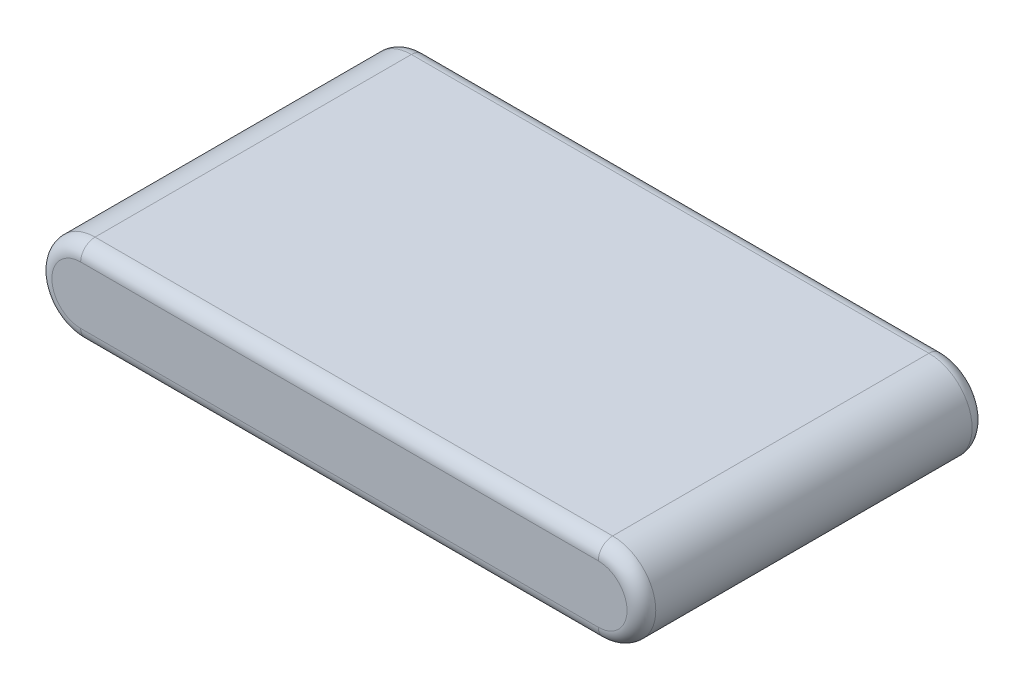
SolidWorks part; units mm, degrees
ref_plane "Plano frontal" through (0, 0, 0) normal (0, 0, 1) x (1, 0, 0)
ref_plane "Plano superior" through (0, 0, 0) normal (0, 1, 0) x (1, 0, 0)
ref_plane "Plano direito" through (0, 0, 0) normal (1, 0, 0) x (0, 0, -1)
sketch "Esboço1" plane through (0, 0, 0) normal (0, 0, 1) x (1, 0, 0)
  line L4 (0, 0) -> (0, 0.8933) construction
  line L7 (9, 0) -> (-9, 0) construction
  line L8 (9, 1.5) -> (-9, 1.5)
  line L9 (9, -1.5) -> (-9, -1.5)
  arc A6 (-9, -1.5) -> (-9, 1.5) centre (-9, 0) cw
  arc A7 (9, 1.5) -> (9, -1.5) centre (9, 0) cw
extrude "Ressalto-extrusão1" add sketch "Esboço1" along normal blind 12
fillet "Filete1" radius 0.5 8 edges at (0, 1.5, 0) (-10.5, 0, 0) (0, -1.5, 0) (10.5, 0, 0) (0, -1.5, 12) (-10.5, 0, 12) (0, 1.5, 12) (10.5, 0, 12)
sketch "Esboço2" plane through (0, 0, 12) normal (0, 0, 1) x (1, 0, 0)
  line L0 (-10.5, 0) -> (10.5, 0) construction
  line L3 (-9, 1.5) -> (9, 1.5) construction
  line L5 (0, 1.5) -> (0, -1.5) construction
  line L6 (9, -1.5) -> (-9, -1.5) construction
  arc A2 (-9, 1.5) -> (-9, -1.5) centre (-9, 0) ccw construction
  arc A3 (9, -1.5) -> (9, 1.5) centre (9, 0) ccw construction
